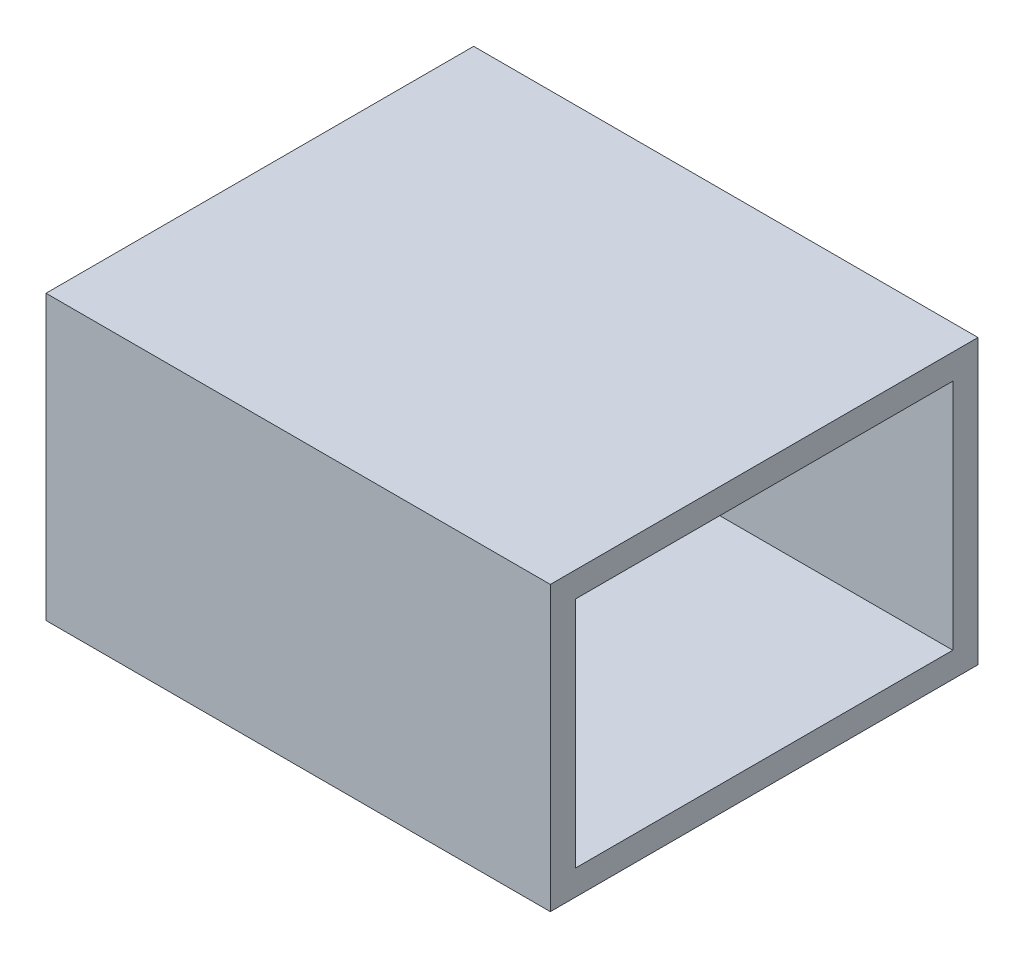
SolidWorks part; units mm, degrees
ref_plane "Front Plane" through (0, 0, 0) normal (0, 0, 1) x (1, 0, 0)
ref_plane "Top Plane" through (0, 0, 0) normal (0, 1, 0) x (1, 0, 0)
ref_plane "Right Plane" through (0, 0, 0) normal (1, 0, 0) x (0, 0, -1)
sketch "Sketch1" plane through (0, 0, 0) normal (1, 0, 0) x (0, 0, -1)
  line L1 (0, 0) -> (189.992, 0)
  line L2 (0, 0) -> (0, -117.348)
  line L3 (0, -117.348) -> (189.992, -117.348)
  line L4 (189.992, 0) -> (189.992, -117.348)
  line L5 (202.692, 12.7) -> (-12.7, 12.7)
  line L6 (202.692, 12.7) -> (202.692, -130.048)
  line L7 (202.692, -130.048) -> (-12.7, -130.048)
  line L8 (-12.7, 12.7) -> (-12.7, -130.048)
  dimension "D1" = 189.992
  dimension "D2" = 117.348
  dimension "D3" = 215.392
  dimension "D4" = 142.748
  dimension "D5" = 12.7
  dimension "D6" = 12.7
extrude "Boss-Extrude1" add sketch "Sketch1" along normal blind 254
